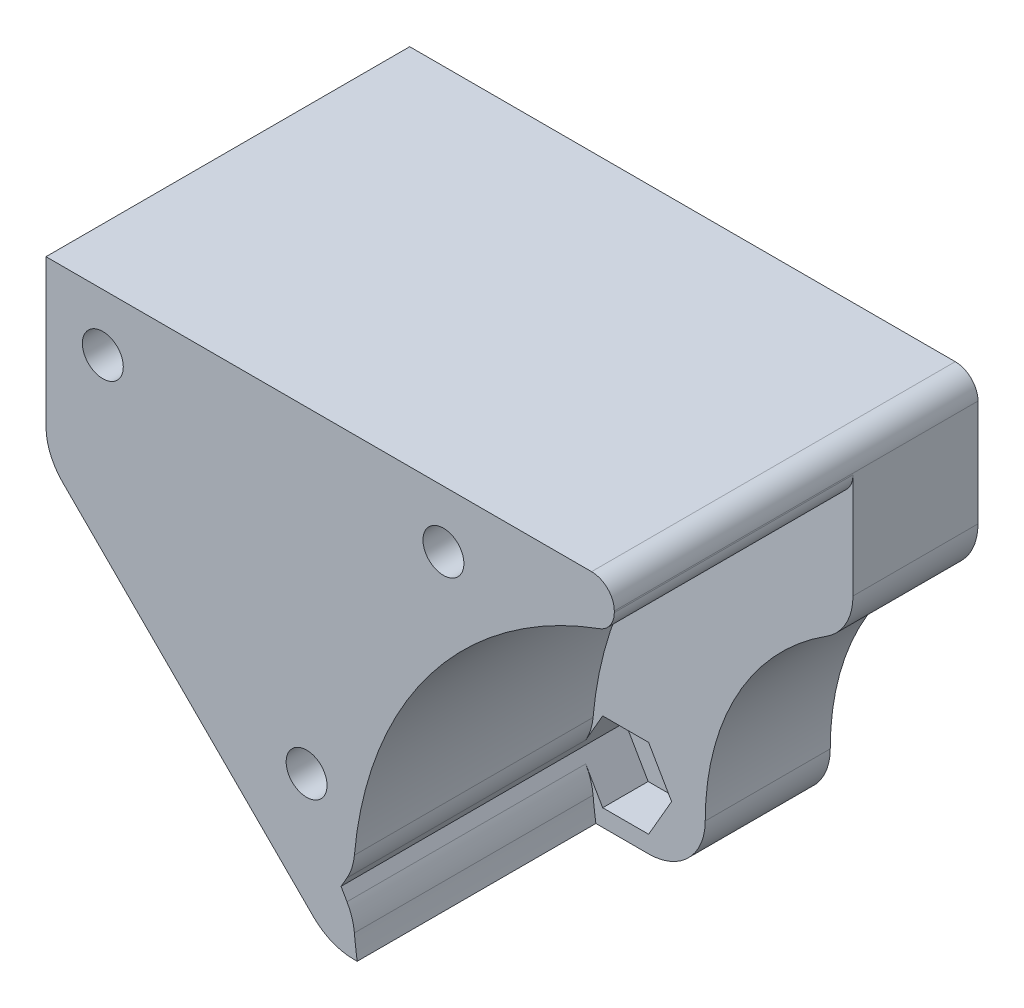
SolidWorks part; units mm, degrees
ref_plane "Front Plane" through (0, 0, 0) normal (0, 0, 1) x (1, 0, 0)
ref_plane "Top Plane" through (0, 0, 0) normal (0, 1, 0) x (1, 0, 0)
ref_plane "Right Plane" through (0, 0, 0) normal (1, 0, 0) x (0, 0, -1)
sketch "Sketch1" plane through (0, 0, 0) normal (0, 0, 1) x (1, 0, 0)
  line L0 (-63.5, 31.75) -> (-31.75, 0)
  line L1 (0, 0) -> (-31.75, 0)
  line L2 (0, 0) -> (0, 50.8)
  line L3 (0, 50.8) -> (-63.5, 50.8)
  line L4 (-63.5, 31.75) -> (-63.5, 50.8)
  circle A0 centre (-57.15, 44.45) radius 2.286
  circle A1 centre (-19.0918, 44.45) radius 2.286
  circle A2 centre (-34.3803, 15.3303) radius 2.286
  point P12 (0, 0)
  point P13 (-47.0803, 15.3303)
  dimension "D8" = 4.572
  dimension "D1" = 50.8
  dimension "D2" = 45
  dimension "D3" = 63.5
  dimension "D4" = 19.05
  dimension "D5" = 6.35
  dimension "D6" = 6.35
  dimension "D7" = 38.0582
  dimension "D9" = 29.1197
  dimension "D10" = 15.3303
extrude "Boss-Extrude1" add sketch "Sketch1" along normal blind 40.64
sketch "Sketch2" plane through (0, 0, 40.64) normal (0, 0, 1) x (1, 0, 0)
  circle A0 centre (12.7, 6.35) radius 41.91
  dimension "D1" = 83.82
extrude "Cut-Extrude1" cut sketch "Sketch2" against normal blind 26.67
sketch "Sketch3" plane through (0, 0, 0) normal (0, 0, -1) x (-1, 0, 0)
  circle A0 centre (-12.7, 6.35) radius 29.21
  dimension "D1" = 58.42
extrude "Cut-Extrude2" cut sketch "Sketch3" against normal through all
sketch "Sketch4" plane through (0, 0, 0) normal (0, 0, -1) x (-1, 0, 0)
  circle A0 centre (25.4, 6.35) radius 2.286
  dimension "D1" = 4.572
extrude "Cut-Extrude3" cut sketch "Sketch4" against normal through all
sketch "Sketch5" plane through (0, 0, 40.64) normal (0, 0, 1) x (1, 0, 0)
  line L1 (-20.2674, 6.35) -> (-22.8337, 10.795)
  line L2 (-22.8337, 10.795) -> (-27.9663, 10.795)
  line L3 (-27.9663, 10.795) -> (-30.5326, 6.35)
  line L4 (-30.5326, 6.35) -> (-27.9663, 1.905)
  line L5 (-27.9663, 1.905) -> (-22.8337, 1.905)
  line L6 (-22.8337, 1.905) -> (-20.2674, 6.35)
  circle A0 centre (-25.4, 6.35) radius 4.445 construction
  dimension "D1" = 8.89
extrude "Cut-Extrude4" cut sketch "Sketch5" against normal offset from surface (31.75 mm away) 8.89 up to face at (-27.686, 6.35, 0)
fillet "Fillet1" radius 6.35 4 edges at (0, 32.6546, 6.985) (-15.8114, 0, 6.985) (-31.75, 0, 20.32) (-63.5, 31.75, 20.32)
fillet "Fillet2" radius 2.54 2 edges at (0, 50.8, 20.32) (0, 46.2894, 27.305)
fillet "Fillet3" radius 6.35 2 edges at (-29.1406, 8.7611, 27.305) (-29.1406, 3.9389, 27.305)
